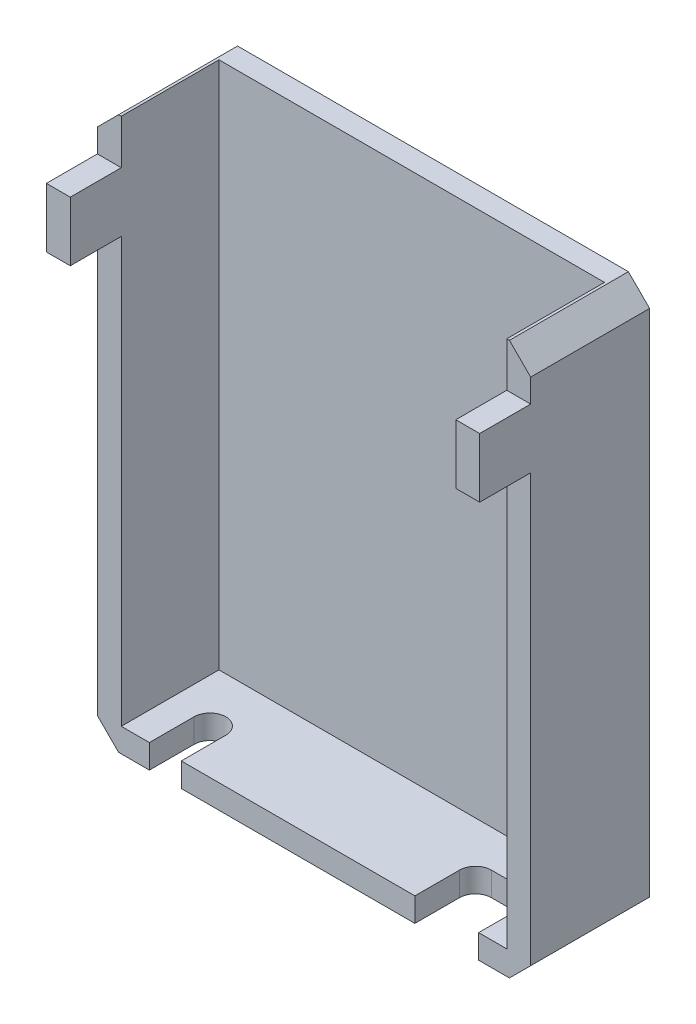
SolidWorks part; units mm, degrees
ref_plane "Front Plane" through (0, 0, 0) normal (0, 0, 1) x (1, 0, 0)
ref_plane "Top Plane" through (0, 0, 0) normal (0, 1, 0) x (1, 0, 0)
ref_plane "Right Plane" through (0, 0, 0) normal (1, 0, 0) x (0, 0, -1)
sketch "Sketch11" plane through (0, 0, 0) normal (0, 0, 1) x (1, 0, 0)
  line L1 (-10.2, 13) -> (10.2, 13)
  line L2 (-10.2, 13) -> (-10.2, -13)
  line L3 (-10.2, -13) -> (10.2, -13)
  line L4 (10.2, 13) -> (10.2, -13)
  line L7 (-10.2, 13) -> (10.2, -13) construction
  dimension "D2" = 20.4
  dimension "D1" = 26
extrude "Boss-Extrude5" add sketch "Sketch11" along normal blind 1 separate body
sketch "Sketch12" plane through (0, 0, 1) normal (0, 0, 1) x (1, 0, 0)
  line L0 (-10.2, 13) -> (-10.2, -13)
  line L1 (-10.2, -13) -> (10.2, -13)
  line L2 (10.2, -13) -> (10.2, 13)
  line L3 (10.2, 13) -> (9.075, 13)
  line L4 (10.2, 13) -> (-10.2, 13) construction
  line L5 (9.075, 13) -> (9.075, -11.875)
  line L6 (9.075, -11.875) -> (-9.075, -11.875)
  line L7 (-9.075, -11.875) -> (-9.075, 13)
  line L8 (-9.075, 13) -> (-10.2, 13)
  line L9 (0, -11.875) -> (0, -13) construction
  line L10 (-10.2, -11.875) -> (-9.075, -11.875) construction
  line L11 (-9.075, -11.875) -> (-9.075, -13) construction
  line L12 (-10.2, -13) -> (10.2, -13) construction
  dimension "D2" = 1.125
extrude "Boss-Extrude6" add sketch "Sketch12" along normal blind 4.6
chamfer "Chamfer2" distance 1 angle 45 4 edges at (-10.2, 13, 2.8) (10.2, 13, 2.8) (10.2, -13, 2.8) (-10.2, -13, 2.8)
sketch "Sketch13" plane through (0, -13, 0) normal (0, -1, 0) x (1, 0, 0)
  line L0 (-9.2, 5.6) -> (9.2, 5.6) construction
  line L2 (-7.75, 5.6) -> (-6.25, 5.6)
  line L3 (-7.75, 5.6) -> (-7.75, 3.5)
  line L4 (7.75, 5.6) -> (4.75, 5.6)
  line L5 (-6.25, 5.6) -> (-6.25, 3.5)
  line L6 (-7.75, 4.25) -> (-7.75, 9) construction
  line L7 (-6.25, 4.25) -> (-6.25, 1) construction
  line L8 (7.75, 4.25) -> (7.75, 9) construction
  line L9 (4.75, 5.6) -> (4.75, 3.5)
  line L10 (4.75, 1) -> (4.75, 4.25) construction
  line L11 (7.75, 3.5) -> (7.75, 5.6)
  line L12 (7, 2.75) -> (5.5, 2.75)
  arc A1 (-7.75, 3.5) -> (-6.25, 3.5) centre (-7, 3.5) ccw
  arc A2 (-6.25, 4.25) -> (-7.75, 4.25) centre (-7, 4.25) ccw construction
  arc A3 (7, 2.75) -> (7.75, 3.5) centre (7, 3.5) ccw
  arc A4 (4.75, 3.5) -> (5.5, 2.75) centre (5.5, 3.5) ccw
extrude "Cut-Extrude1" cut sketch "Sketch13" against normal up to next
sketch "Sketch14" plane through (0, 0, 5.6) normal (0, 0, 1) x (1, 0, 0)
  line L0 (-10.2, 12) -> (-10.2, -12) construction
  line L1 (-10.2, 10.9) -> (-9.075, 10.9)
  line L2 (-10.2, 10.9) -> (-10.2, 8.1)
  line L3 (-10.2, 8.1) -> (-9.075, 8.1)
  line L4 (-9.075, 10.9) -> (-9.075, 8.1)
  line L5 (-9.075, -11.875) -> (-9.075, 13) construction
  line L6 (9.075, 13) -> (9.075, -11.875) construction
  line L7 (9.075, 10.9) -> (10.2, 10.9)
  line L8 (9.075, 10.9) -> (9.075, 8.1)
  line L9 (9.075, 8.1) -> (10.2, 8.1)
  line L10 (10.2, 10.9) -> (10.2, 8.1)
  line L11 (10.2, -12) -> (10.2, 12) construction
  line L12 (-10.2, 11) -> (-9.025, 11) construction
  line L13 (-9.025, 8) -> (-10.2, 8) construction
  dimension "D1" = 0.1
  dimension "D2" = 0.1
extrude "Boss-Extrude7" add sketch "Sketch14" along normal offset from surface (2.4 mm away) 0.1
